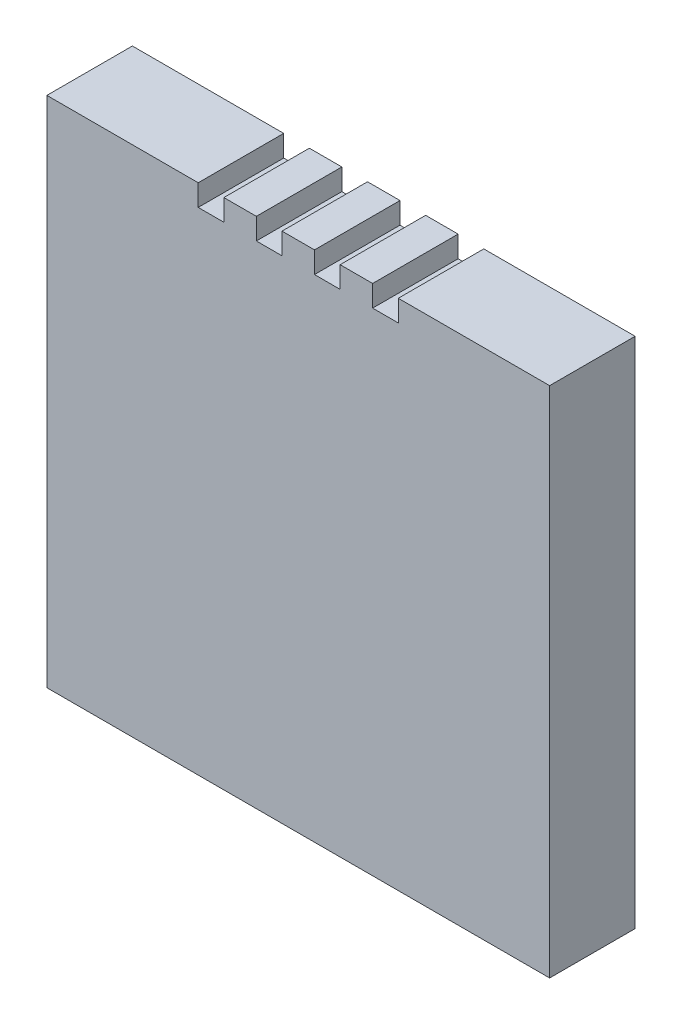
SolidWorks part; units mm, degrees
ref_plane "Front Plane" through (0, 0, 0) normal (0, 0, 1) x (1, 0, 0)
ref_plane "Top Plane" through (0, 0, 0) normal (0, 1, 0) x (1, 0, 0)
ref_plane "Right Plane" through (0, 0, 0) normal (1, 0, 0) x (0, 0, -1)
sketch "Sketch1" plane through (0, 0, 0) normal (0, 0, 1) x (1, 0, 0)
  line L1 (-10.5, -6) -> (10.5, -6)
  line L2 (-10.5, -6) -> (-10.5, 6)
  line L4 (10.5, -6) -> (10.5, 6)
  line L5 (-10.5, -6) -> (10.5, 6) construction
  line L6 (-10.5, 6) -> (10.5, -6) construction
  line L8 (-2.34, 6) -> (-2.34, 10.8354) construction
  line L9 (-2.34, 10.8354) -> (-1.74, 10.8354) construction
  line L10 (-1.74, 10.8354) -> (-1.74, 6) construction
  line L13 (-0.98, 6) -> (-0.98, 10.8354) construction
  line L14 (-0.98, 10.8354) -> (-0.38, 10.8354) construction
  line L15 (-0.38, 10.8354) -> (-0.38, 6) construction
  line L18 (0.38, 6) -> (0.38, 10.8354) construction
  line L19 (0.38, 10.8354) -> (0.98, 10.8354) construction
  line L20 (0.98, 10.8354) -> (0.98, 6) construction
  line L23 (1.74, 6) -> (1.74, 10.8354) construction
  line L24 (1.74, 10.8354) -> (2.34, 10.8354) construction
  line L25 (2.34, 10.8354) -> (2.34, 6) construction
  line L26 (-10.5, 6) -> (-2.34, 6)
  line L27 (-1.74, 6) -> (-0.98, 6)
  line L28 (-0.38, 6) -> (0.38, 6)
  line L29 (0.98, 6) -> (1.74, 6)
  line L30 (2.34, 6) -> (10.5, 6)
  line L31 (-2.34, 10.8354) -> (2.34, 10.8354) construction
  line L32 (8.5, -2.5) -> (-8.5, -2.5) construction
  line L33 (-8.5, -2.5) -> (-8.5, 2.5) construction
  line L34 (-2.34, 6) -> (-2.34, 5.5)
  line L35 (-2.34, 5.5) -> (-1.74, 5.5)
  line L36 (-1.74, 5.5) -> (-1.74, 6)
  line L37 (-0.98, 6) -> (-0.98, 5.5)
  line L38 (-0.98, 5.5) -> (-0.38, 5.5)
  line L39 (-0.38, 5.5) -> (-0.38, 6)
  line L40 (0.38, 6) -> (0.38, 5.5)
  line L41 (0.38, 5.5) -> (0.98, 5.5)
  line L42 (0.98, 5.5) -> (0.98, 6)
  line L43 (1.74, 6) -> (1.74, 5.5)
  line L44 (1.74, 5.5) -> (2.34, 5.5)
  line L45 (2.34, 5.5) -> (2.34, 6)
  circle A0 centre (8.5, -2.5) radius 1.5
  circle A1 centre (-8.5, -2.5) radius 1.5
  point P0 (0, 0)
  point P7 (-0.68, 5.5)
  point P12 (0, 10.8354)
  point P13 (0, -6)
  point P15 (-2.04, 5.5)
  point P37 (0, -2.5)
  point P38 (-8.5, 0)
  dimension "D6" = 3
  dimension "D1" = 21
  dimension "D2" = 12
  dimension "D3" = 0.6
  dimension "D4" = 1.36
  dimension "D7" = 0.5
  dimension "D8" = 17
  dimension "D9" = 8.5
  dimension "D5" = 4
extrude "Boss-Extrude1" add sketch "Sketch1" along normal blind 2
sketch "Sketch3" plane through (0, 6, 0) normal (0, 1, 0) x (1, 0, 0)
  line L1 (10.5, 0) -> (5.88, 0)
  line L2 (10.5, 0) -> (10.5, -2.6725)
  line L3 (10.5, -2.6725) -> (5.88, -2.6725)
  line L4 (5.88, 0) -> (5.88, -2.6725)
  line L5 (-10.5, 0) -> (-5.88, 0)
  line L6 (-10.5, 0) -> (-10.5, -3.0634)
  line L7 (-10.5, -3.0634) -> (-5.88, -3.0634)
  line L8 (-5.88, 0) -> (-5.88, -3.0634)
  dimension "D1" = 11.76
extrude "Cut-Extrude2" cut sketch "Sketch3" against normal through all both and the other way through all
